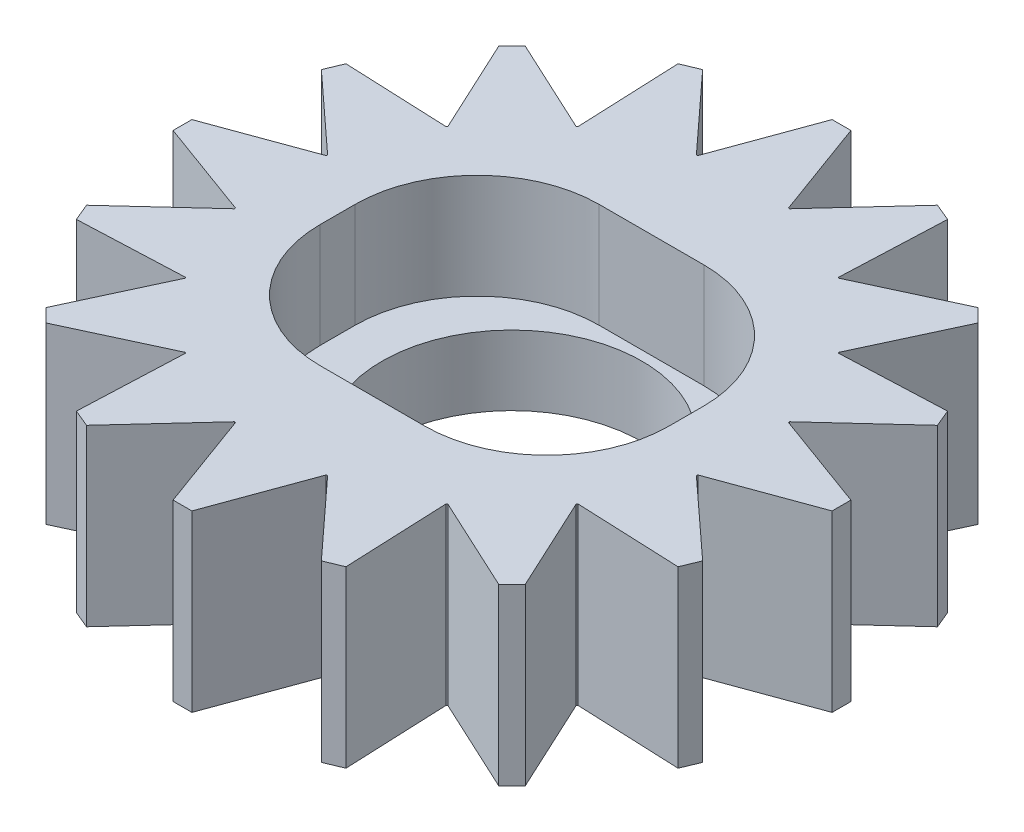
SolidWorks part; units mm, degrees
ref_plane "Front Plane" through (0, 0, 0) normal (0, 0, 1) x (1, 0, 0)
ref_plane "Top Plane" through (0, 0, 0) normal (0, 1, 0) x (1, 0, 0)
ref_plane "Right Plane" through (0, 0, 0) normal (1, 0, 0) x (0, 0, -1)
sketch "Sketch2" plane through (0, 0, 0) normal (0, 1, 0) x (1, 0, 0)
  line L0 (0, 6.75) -> (0, -22.3339) construction
  line L1 (6.75, 0) -> (-25.2541, 0) construction
  circle A0 centre (0, 0) radius 6.75
  dimension "D1" = 13.5
extrude "Boss-Extrude1" add sketch "Sketch2" along normal blind 5
sketch "Sketch3" plane through (0, 5, 0) normal (0, 1, 0) x (1, 0, 0)
  line L1 (-5, 4) -> (5, 4)
  line L2 (-5, 4) -> (-5, -4)
  line L3 (-5, -4) -> (5, -4)
  line L4 (5, 4) -> (5, -4)
  line L5 (-5, 4) -> (5, -4) construction
  line L6 (-5, -4) -> (5, 4) construction
  point P0 (0, 0)
  dimension "D1" = 10
  dimension "D2" = 8
extrude "Cut-Extrude1" cut sketch "Sketch3" against normal blind 3
fillet "Fillet1" radius 3.5 4 edges at (-5, 3.5, 4) (5, 3.5, 4) (-5, 3.5, -4) (5, 3.5, -4)
sketch "Sketch4" plane through (0, 2, 0) normal (0, 1, 0) x (1, 0, 0)
  line L1 (1.5, 4) -> (-1.5, 4) construction
  line L2 (0, 0) -> (0, -17.2909) construction
  circle A0 centre (0, 0) radius 3.725
  dimension "D1" = 7.45
  dimension "D3" = 4
extrude "Cut-Extrude2" cut sketch "Sketch4" against normal through all
ref_plane "Plane1" through (0, 5, 0) normal (0, 1, 0) x (1, 0, 0)
sketch "Sketch5" plane through (0, 5, 0) normal (0, 1, 0) x (1, 0, 0)
  line L0 (0, 0) -> (0, 13.0768) construction
  line L1 (0, 0) -> (17.6113, 0) construction
  line L2 (-1.3001, 6.6236) -> (-0.2697, 9.442)
  line L3 (-0.2697, 9.442) -> (0.2697, 9.442)
  line L4 (0.2697, 9.442) -> (1.3001, 6.6236)
  line L5 (1.3001, 6.6236) -> (-1.3001, 6.6236)
  line L6 (-0.2697, -9.442) -> (-1.3001, -6.6236)
  line L7 (1.3001, -6.6236) -> (0.2697, -9.442)
  line L8 (0.2697, -9.442) -> (-0.2697, -9.442)
  line L9 (-1.3001, -6.6236) -> (1.3001, -6.6236)
  circle A0 centre (0, 0) radius 6.75 construction
  point P126 (0, 0)
  dimension "D1" = 2
extrude "Boss-Extrude2" add sketch "Sketch5" against normal blind 5
pattern_circular "CirPattern1" count 16 over 360 about axis through (0, 0, 0) along (0, 1, 0) of "Boss-Extrude2"
